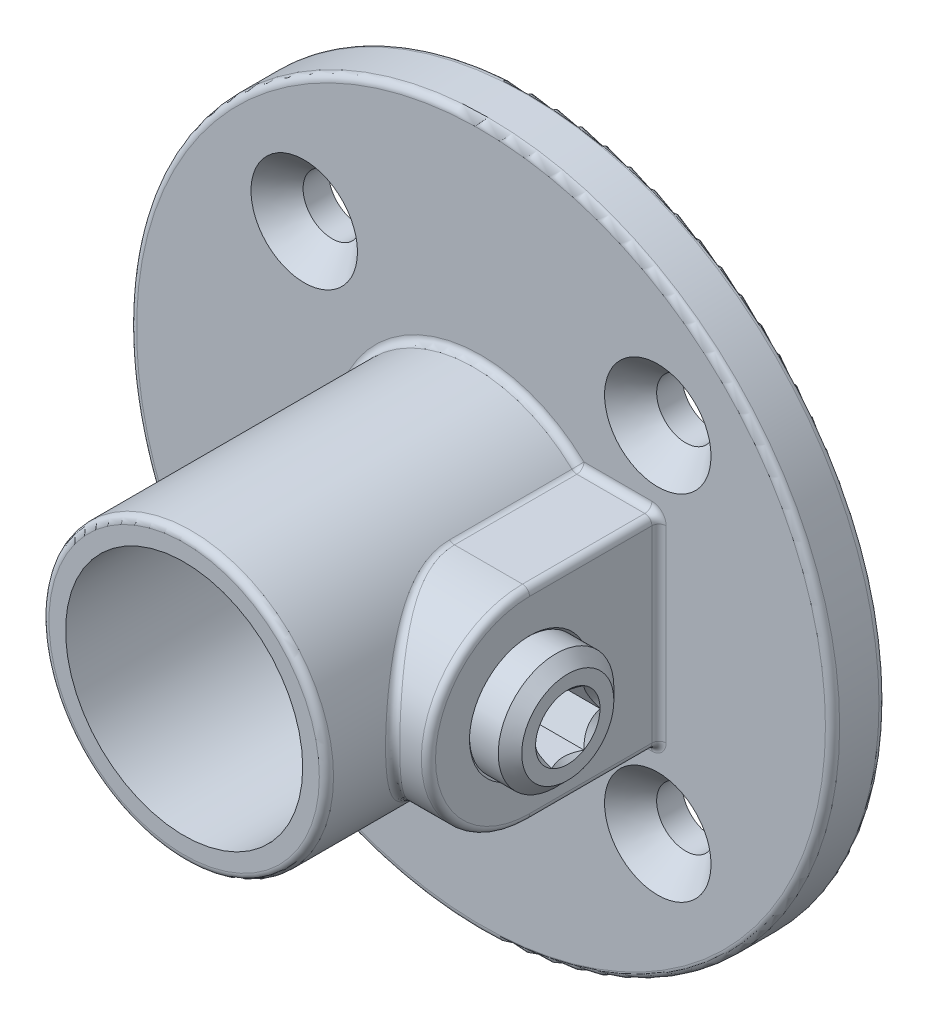
SolidWorks part; units mm, degrees
ref_plane "Front Plane" through (0, 0, 0) normal (0, 0, 1) x (1, 0, 0)
ref_plane "Top Plane" through (0, 0, 0) normal (0, 1, 0) x (1, 0, 0)
ref_plane "Right Plane" through (0, 0, 0) normal (1, 0, 0) x (0, 0, -1)
sketch "Sketch1" plane through (0, 0, 0) normal (1, 0, 0) x (0, 0, -1)
  line L0 (0, 0) -> (-39.878, 0) construction
  line L1 (0, 40.005) -> (0, -40.005) construction
  line L2 (0, 28.448) -> (0, -28.448) construction
  line L3 (0, 31.75) -> (0, 25.146) construction
  line L4 (-39.878, 13.4937) -> (-39.878, -13.4938) construction
  line L5 (-39.878, 16.1925) -> (-39.878, -16.1925) construction
  point P5 (-6.096, 0)
  point P14 (-3.048, 0)
  dimension "D1" = 32.385
  dimension "D2" = 2.6988
  dimension "D3" = 3.048
sketch "Sketch2" plane through (0, 0, 0) normal (0, 0, 1) x (1, 0, 0)
  line L0 (-20.1158, 23.4178) -> (-20.1158, 16.8138) construction
  line L1 (-20.1158, 20.1158) -> (20.1158, -20.1158) construction
  line L2 (20.1158, 20.1158) -> (-20.1158, -20.1158) construction
  line L3 (0, 28.448) -> (0, -28.448) construction
  line L4 (0, 31.75) -> (0, 25.146) construction
  circle A0 centre (0, 0) radius 40.005
  circle A1 centre (0, 0) radius 28.448 construction
  circle A2 centre (-20.1158, 20.1158) radius 3.302 construction
  circle A3 centre (20.1158, 20.1158) radius 3.302 construction
  circle A4 centre (20.1158, -20.1158) radius 3.302 construction
  circle A5 centre (-20.1158, -20.1158) radius 3.302 construction
  dimension "D1" = 45
extrude "Boss-Extrude1" add sketch "Sketch2" along normal up to vertex (6.096 mm away) up to point (0, 0, 6.096)
sketch "Sketch3" plane through (0, 0, 6.096) normal (0, 0, 1) x (1, 0, 0)
  line L0 (0, 0) -> (16.1925, 0) construction
  circle A0 centre (0, 0) radius 16.1925
extrude "Boss-Extrude2" add sketch "Sketch3" along normal up to vertex (33.782 mm away) up to point (0, 16.1925, 39.878)
sketch "Sketch4" plane through (0, 0, 39.878) normal (0, 0, 1) x (1, 0, 0)
  line L0 (0, 0) -> (13.4938, 0) construction
  circle A0 centre (0, 0) radius 13.4938
extrude "Cut-Extrude1" cut sketch "Sketch4" against normal up to vertex (36.83 mm away) up to point (0, 0, 3.048)
sketch "Sketch5" plane through (0, 0, 3.048) normal (0, 0, 1) x (1, 0, 0)
  circle A2 centre (0, 0) radius 10.4458
  circle A3 centre (0, 0) radius 10.4458
  dimension "D1" = 3.048
extrude "Cut-Extrude2" cut sketch "Sketch5" against normal up to vertex (3.048 mm away) up to point (0, 0, 0)
ref_plane "Plane1" through (16.1925, 0, 0) normal (1, 0, 0) x (0, 0, -1)
ref_plane "Plane2" through (20.2565, 0, 0) normal (1, 0, 0) x (0, 0, -1)
sketch "Sketch6" plane through (20.2565, 0, 0) normal (1, 0, 0) x (0, 0, -1)
  line L0 (-20.828, 0) -> (-39.878, 0) construction
  line L2 (-20.828, 11.5125) -> (-6.096, 11.5125)
  line L3 (-20.828, -11.5125) -> (-6.096, -11.5125)
  line L4 (-6.096, -11.5125) -> (-6.096, 11.5125)
  circle A0 centre (-20.828, 0) radius 6.5786 construction
  arc A1 (-20.828, 11.5125) -> (-20.828, -11.5125) centre (-20.828, 0) ccw
  dimension "D2" = 23.0251
extrude "Boss-Extrude3" add sketch "Sketch6" against normal up to next
sketch "Sketch7" plane through (20.2565, 0, 0) normal (1, 0, 0) x (0, 0, -1)
  circle A0 centre (-20.828, 0) radius 6.5786 construction
  circle A1 centre (-20.828, 0) radius 6.5786
extrude "Cut-Extrude3" cut sketch "Sketch7" against normal up to next
chamfer "Chamfer1" distance 0.254 angle 45 1 edges at (20.2565, 0, 14.2494)
ref_plane "Plane3" through (13.4938, 0, 0) normal (1, 0, 0) x (0, 0, -1)
sketch "Sketch8" plane through (13.4938, 0, 0) normal (1, 0, 0) x (0, 0, -1)
  circle A0 centre (-20.828, 0) radius 6.5786 construction
  circle A1 centre (-20.828, 0) radius 6.5786
extrude "Boss-Extrude4" add sketch "Sketch8" along normal blind 12.7 from offset 1.5875 separate body offset against normal yes
chamfer "Chamfer2" distance 1.3368 angle 45 2 edges at (11.9062, 0, 14.2494) (24.6062, 0, 14.2494)
sketch "Sketch9" plane through (24.6062, 0, 0) normal (1, 0, 0) x (0, 0, -1)
  line L1 (-17.1618, 0) -> (-18.9949, 3.175)
  line L2 (-18.9949, 3.175) -> (-22.6611, 3.175)
  line L3 (-22.6611, 3.175) -> (-24.4942, 0)
  line L4 (-24.4942, 0) -> (-22.6611, -3.175)
  line L5 (-22.6611, -3.175) -> (-18.9949, -3.175)
  line L6 (-18.9949, -3.175) -> (-17.1618, 0)
  circle A0 centre (-20.828, 0) radius 3.175 construction
  dimension "Screw Hex" = 6.35
extrude "Cut-Extrude4" cut sketch "Sketch9" against normal up to next (12.7 mm away)
sketch "Sketch10" plane through (24.6062, 0, 0) normal (1, 0, 0) x (0, 0, -1)
  circle A0 centre (-20.828, 0) radius 3.6662
extrude "Cut-Extrude5" cut sketch "Sketch10" against normal through all draft 45
sketch "Sketch11" plane through (0, 0, 0) normal (0, 0, -1) x (-1, 0, 0)
  circle A0 centre (20.1158, 20.1158) radius 3.302 construction
  circle A1 centre (-20.1158, 20.1158) radius 3.302 construction
  circle A2 centre (20.1158, -20.1158) radius 3.302 construction
  circle A3 centre (-20.1158, -20.1158) radius 3.302 construction
  circle A4 centre (20.1158, 20.1158) radius 3.302
  circle A5 centre (-20.1158, 20.1158) radius 3.302
  circle A6 centre (20.1158, -20.1158) radius 3.302
  circle A7 centre (-20.1158, -20.1158) radius 3.302
extrude "Cut-Extrude6" cut sketch "Sketch11" against normal up to vertex (6.096 mm away) up to point (0, 0, 6.096)
sketch "Sketch12" plane through (0, 0, 6.096) normal (0, 0, 1) x (1, 0, 0)
  circle A0 centre (-20.1158, 20.1158) radius 6.0579
  circle A1 centre (20.1158, 20.1158) radius 6.0579
  circle A2 centre (20.1158, -20.1158) radius 6.0579
  circle A3 centre (-20.1158, -20.1158) radius 6.0579
  dimension "Screw Head OD" = 12.1158
extrude "Cut-Extrude7" cut sketch "Sketch12" against normal through all draft 41
fillet "Fillet1" radius 0.8096 16 edges at (16.1925, 0, 39.878) (40.005, 0, 0) (40.005, 0, 6.096) (-16.1925, 0, 6.096) (13.4938, 0, 3.048) (20.2565, 11.5125, 13.462) (20.2565, -11.5125, 13.462) (11.3868, 11.5125, 13.462) (11.3868, -11.5125, 13.462) (20.2565, 0, 32.3406) (16.181, 0.6096, 32.3244) (15.8216, 11.5125, 6.096) (15.8216, -11.5125, 6.096) (20.2565, 0, 6.096) (10.4458, 0, 0) (10.4458, 0, 3.048)
equation "\"D1@Sketch1\" = \"Fitting ID@Sketch1\" * 1.2"
equation "\"D3@Sketch1\" = \"D@Sketch1\" / 2"
equation "\"D1@Sketch5\" = \"D3@Sketch1\""
equation "\"D1@Fillet1\" = \"D2@Sketch1\" * 0.3"
equation "\"D1@Plane2\" = \"D@Sketch1\" / 1.5"
equation "\"D2@Sketch6\" = \"Screw OD@Sketch6\" * 1.75"
